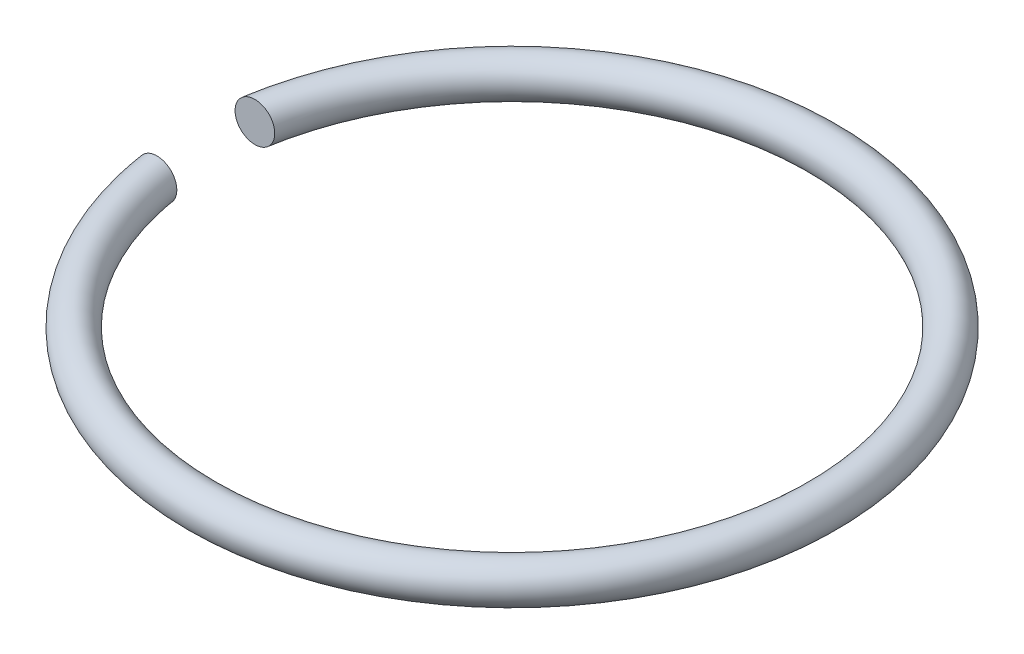
SolidWorks part; units mm, degrees
material "1.5805 (10NiCr5-4)"
ref_plane "Спереди" through (0, 0, 0) normal (0, 0, 1) x (1, 0, 0)
ref_plane "Сверху" through (0, 0, 0) normal (0, 1, 0) x (1, 0, 0)
ref_plane "Справа" through (0, 0, 0) normal (1, 0, 0) x (0, 0, -1)
sketch "Эскиз1" plane through (0, 0, 0) normal (0, 0, 1) x (1, 0, 0)
  line L0 (0, 0) -> (0, 5.376) construction
  circle A0 centre (-9.5, 0) radius 0.6
  dimension "D1" = 1.2
  dimension "D2" = 9.5
revolve "Повернуть1" add sketch "Эскиз1" angle 360 about L0
sketch "Эскиз2" plane through (0, 0, 0) normal (0, 1, 0) x (1, 0, 0)
  line L0 (0, 0) -> (-16.7656, 0) construction
  line L1 (-12.162, 1.5) -> (-7.1672, 1.5)
  line L2 (-12.162, 1.5) -> (-12.162, -1.5)
  line L3 (-12.162, -1.5) -> (-7.1672, -1.5)
  line L4 (-7.1672, 1.5) -> (-7.1672, -1.5)
  dimension "D1" = 1.5
  dimension "D2" = 1.5
extrude "Вырез-Вытянуть1" cut sketch "Эскиз2" against normal through all and the other way through all
